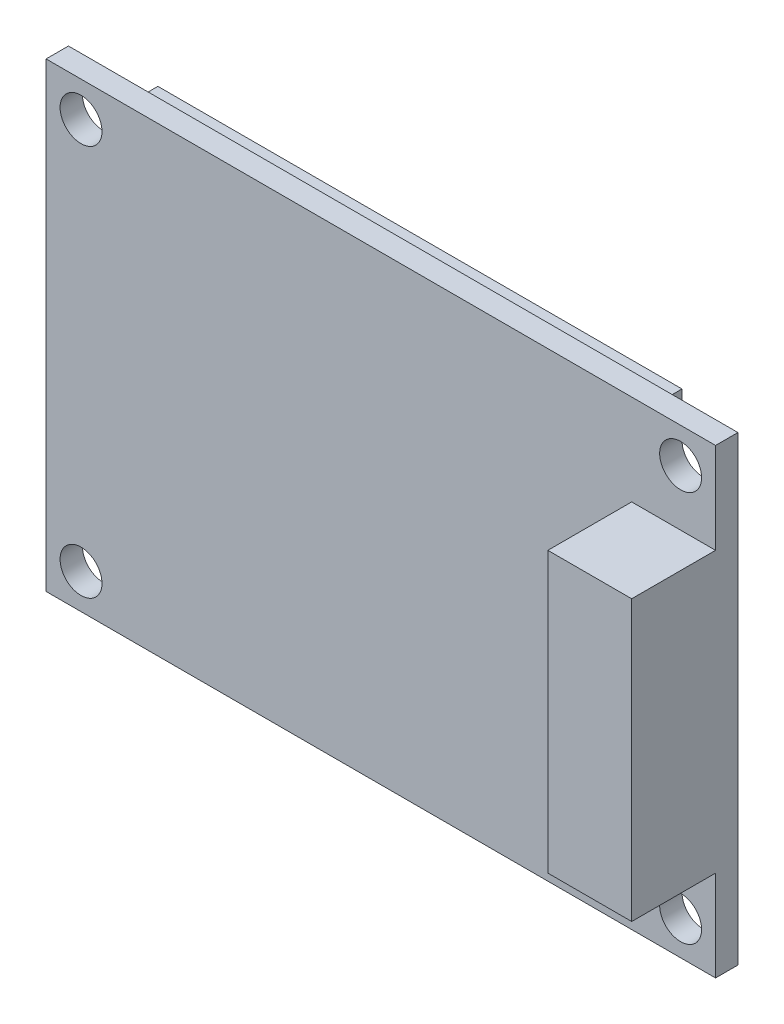
SolidWorks part; units mm, degrees
ref_plane "Plan de face" through (0, 0, 0) normal (0, 0, 1) x (1, 0, 0)
ref_plane "Plan de dessus" through (0, 0, 0) normal (0, 1, 0) x (1, 0, 0)
ref_plane "Plan de droite" through (0, 0, 0) normal (1, 0, 0) x (0, 0, -1)
sketch "BASE PCB" plane through (0, 0, 0) normal (0, 0, 1) x (1, 0, 0)
  line L0 (0, -55) -> (0, 55) construction
  line L1 (23.95, 16.5) -> (-23.95, 16.5)
  line L2 (23.95, 16.5) -> (23.95, -16.5)
  line L3 (23.95, -16.5) -> (-23.95, -16.5)
  line L4 (-23.95, 16.5) -> (-23.95, -16.5)
  line L5 (23.95, 16.5) -> (-23.95, -16.5) construction
  line L6 (23.95, -16.5) -> (-23.95, 16.5) construction
  line L8 (23.95, 10) -> (17.95, 10) construction
  line L9 (23.95, 10) -> (23.95, -10) construction
  line L10 (23.95, -10) -> (17.95, -10) construction
  line L11 (17.95, 10) -> (17.95, -10) construction
  circle A0 centre (-21.45, 14) radius 1.5
  circle A1 centre (-21.45, -14) radius 1.5
  circle A2 centre (21.45, -14) radius 1.5
  circle A3 centre (21.45, 14) radius 1.5
  point P0 (0, 0)
  point P10 (23.95, 0)
  point P21 (23.95, 0)
  dimension "D3" = 3
  dimension "D4" = 2.5
  dimension "D1" = 47.9
  dimension "D2" = 33
  dimension "D5" = 2.5
  dimension "D6" = 2.5
  dimension "D7" = 6
  dimension "D8" = 20
extrude "Base_PCB" add sketch "BASE PCB" along normal blind 1.6
sketch "Esquisse4" plane through (0, 0, 0) normal (0, 0, 1) x (1, 0, 0)
  line L1 (18.75, 16) -> (-18.75, 16)
  line L2 (18.75, 16) -> (18.75, -16)
  line L3 (18.75, -16) -> (-18.75, -16)
  line L4 (-18.75, 16) -> (-18.75, -16)
  line L5 (18.75, 16) -> (-18.75, -16) construction
  line L6 (18.75, -16) -> (-18.75, 16) construction
  point P0 (0, 0)
  dimension "D1" = 32
  dimension "D2" = 37.5
extrude "E-Ink_display" add sketch "Esquisse4" against normal blind 1.2
sketch "Esquisse5" plane through (0, 0, -1.2) normal (0, 0, -1) x (-1, 0, 0)
  line L1 (-16.75, -13.8) -> (10.85, -13.8)
  line L2 (-16.75, -13.8) -> (-16.75, 13.8)
  line L3 (-16.75, 13.8) -> (10.85, 13.8)
  line L4 (10.85, -13.8) -> (10.85, 13.8)
  line L7 (-18.75, -16) -> (-18.75, 16) construction
  point P6 (10.85, 0)
  dimension "D1" = 27.6
  dimension "D2" = 2
extrude "Display_200*200" cut sketch "Esquisse5" against normal blind 0.5
sketch "Esquisse6" plane through (0, 0, 1.6) normal (0, 0, 1) x (1, 0, 0)
  line L1 (17.95, 10) -> (23.95, 10)
  line L2 (17.95, 10) -> (17.95, -10)
  line L3 (17.95, -10) -> (23.95, -10)
  line L4 (23.95, 10) -> (23.95, -10)
extrude "Connecteur_8broches" add sketch "Esquisse6" along normal blind 6
